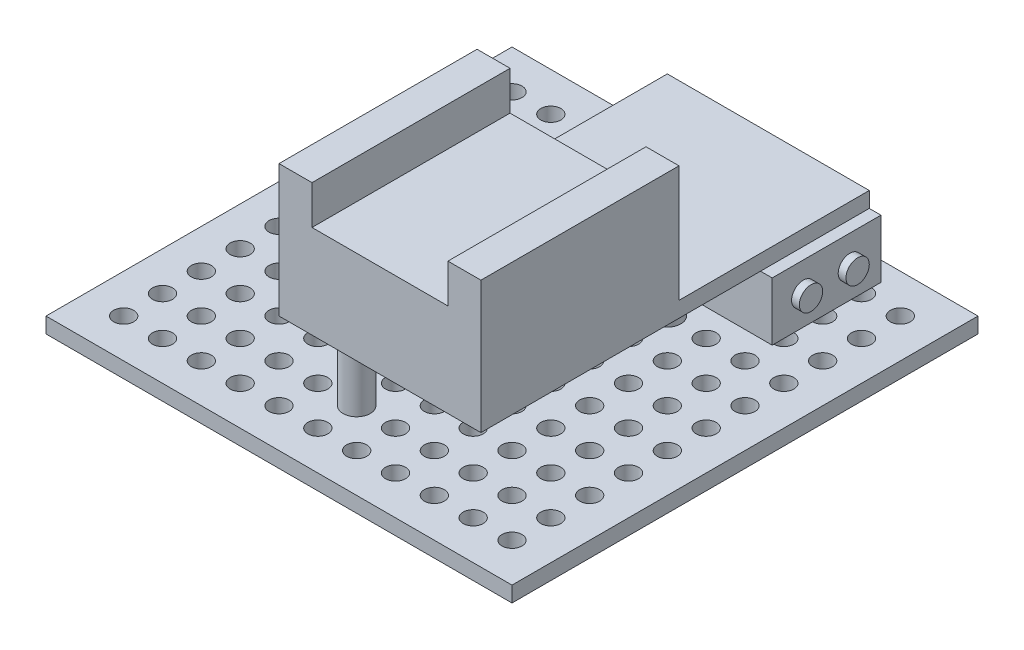
SolidWorks part; units mm, degrees
ref_plane "Front Plane" through (0, 0, 0) normal (0, 0, 1) x (1, 0, 0)
ref_plane "Top Plane" through (0, 0, 0) normal (0, 1, 0) x (1, 0, 0)
ref_plane "Right Plane" through (0, 0, 0) normal (1, 0, 0) x (0, 0, -1)
sketch "Sketch1" plane through (0, 0, 0) normal (0, 1, 0) x (1, 0, 0)
  line L1 (-60, -60) -> (60, -60)
  line L2 (-60, -60) -> (-60, 60)
  line L3 (-60, 60) -> (60, 60)
  line L4 (60, -60) -> (60, 60)
  line L5 (-60, -60) -> (60, 60) construction
  line L6 (-60, 60) -> (60, -60) construction
  point P0 (0, 0)
  dimension "D1" = 120
  dimension "D2" = 120
extrude "Boss-Extrude1" add sketch "Sketch1" along normal blind 4
hole_wizard "13/64 (0.20313) Diameter Hole1" positions "Sketch2" profile "Sketch3" hole size "13/64" standard "ANSI Inch" end condition up to next
sketch "Sketch2" plane through (0, 4, 0) normal (0, 1, 0) x (1, 0, 0)
  line L0 (-60, 60) -> (-60, -60) construction
  line L1 (60, 60) -> (-60, 60) construction
  point P0 (-50, 50)
  dimension "D1" = 10
  dimension "D2" = 10
sketch "Sketch3" plane through (-50, 4, -50) normal (1, 0, 0) x (0, 0, 1)
  line L0 (0, 0) -> (0, 4)
  line L1 (0, 4) -> (2.5798, 4)
  line L2 (2.5798, 4) -> (2.5798, 0)
  line L5 (2.5798, 0) -> (0, 0)
  line L11 (0, -6.35) -> (0, 107.95) construction
  dimension "Thru Hole Dia." = 5.1595
  dimension "Thru Hole Depth" = 4
pattern_linear "LPattern1" count 11 spacing 10 along (0, 0, 1) count 11 spacing 10 along (1, 0, 0) of "13/64 (0.20313) Diameter Hole1"
sketch "Sketch4" plane through (0, 4, 0) normal (0, 1, 0) x (1, 0, 0)
  line L0 (60, -60) -> (60, 60) construction
  line L1 (-60, -60) -> (60, -60) construction
  circle A0 centre (0, -40) radius 3.5
  circle A1 centre (0, 20) radius 3.5
  circle A2 centre (20, 20) radius 3.5
  point P10 (0, 0)
  point P11 (0, 0)
  dimension "D2" = 7
  dimension "D1" = 60
  dimension "D3" = 20
  dimension "D4" = 60
  dimension "D5" = 20
extrude "Boss-Extrude2" add sketch "Sketch4" along normal blind 20
sketch "Sketch5" plane through (0, 24, 0) normal (0, 1, 0) x (1, 0, 0)
  line L0 (60, -60) -> (60, 60) construction
  line L1 (-10, 50) -> (42, 50)
  line L2 (-10, 50) -> (-10, -50)
  line L3 (-10, -50) -> (42, -50)
  line L4 (42, 50) -> (42, -50)
  line L5 (-10, 50) -> (42, -50) construction
  line L6 (-10, -50) -> (42, 50) construction
  line L7 (-60, -60) -> (60, -60) construction
  point P4 (16, 0)
  point P5 (23.5, -3.5)
  dimension "D1" = 52
  dimension "D2" = 100
  dimension "D3" = 18
  dimension "D4" = 10
extrude "Boss-Extrude3" add sketch "Sketch5" along normal blind 4
sketch "Sketch6" plane through (0, 28, 0) normal (0, 1, 0) x (1, 0, 0)
  line L0 (42, -50) -> (42, 50) construction
  line L1 (-10, -50) -> (42, -50)
  line L2 (-10, -50) -> (-10, 1)
  line L3 (-10, 1) -> (42, 1)
  line L4 (42, -50) -> (42, 1)
  line L5 (-10, -50) -> (42, 1) construction
  line L6 (-10, 1) -> (42, -50) construction
  point P4 (16, -24.5)
  dimension "D1" = 51
extrude "Boss-Extrude4" add sketch "Sketch6" along normal blind 30
sketch "Sketch7" plane through (0, 58, 0) normal (0, 1, 0) x (1, 0, 0)
  line L0 (42, 1) -> (-10, 1) construction
  line L1 (-1.5, 1) -> (33.5, 1)
  line L2 (-1.5, 1) -> (-1.5, -50)
  line L3 (-1.5, -50) -> (33.5, -50)
  line L4 (33.5, 1) -> (33.5, -50)
  line L5 (-1.5, 1) -> (33.5, -50) construction
  line L6 (-1.5, -50) -> (33.5, 1) construction
  line L7 (-10, -50) -> (42, -50) construction
  point P4 (16, -24.5)
  point P9 (16, -50)
  dimension "D1" = 35
extrude "Cut-Extrude1" cut sketch "Sketch7" against normal blind 10
sketch "Sketch8" plane through (0, 4, 0) normal (0, 1, 0) x (1, 0, 0)
  line L0 (-31.9, 0) -> (31.9, 0) construction
  line L1 (5, 10) -> (-30, 10)
  line L2 (5, 10) -> (5, -10)
  line L3 (5, -10) -> (-30, -10)
  line L4 (-30, 10) -> (-30, -10)
  line L5 (5, 10) -> (-30, -10) construction
  line L6 (5, -10) -> (-30, 10) construction
  line L7 (-60, 60) -> (-60, -60) construction
  point P4 (-12.5, 0)
  point P5 (0, 0)
  dimension "D1" = 35
  dimension "D2" = 20
  dimension "D3" = 30
extrude "Boss-Extrude5" add sketch "Sketch8" along normal blind 4
sketch "Sketch9" plane through (0, 8, 0) normal (0, 1, 0) x (1, 0, 0)
  line L1 (-3.5, 3.5) -> (3.5, 3.5)
  line L2 (-3.5, 3.5) -> (-3.5, -3.5)
  line L3 (-3.5, -3.5) -> (3.5, -3.5)
  line L4 (3.5, 3.5) -> (3.5, -3.5)
  line L5 (-3.5, 3.5) -> (3.5, -3.5) construction
  line L6 (-3.5, -3.5) -> (3.5, 3.5) construction
  point P0 (0, 0)
  point P5 (0, 0)
  dimension "D1" = 7
extrude "Boss-Extrude6" add sketch "Sketch9" along normal blind 2
sketch "Sketch10" plane through (0, 4, 0) normal (0, 1, 0) x (1, 0, 0)
  line L0 (60, -60) -> (60, 60) construction
  line L1 (-5, 27) -> (40, 27)
  line L2 (-5, 27) -> (-5, 55)
  line L3 (-5, 55) -> (40, 55)
  line L4 (40, 27) -> (40, 55)
  line L5 (-5, 27) -> (40, 55) construction
  line L6 (-5, 55) -> (40, 27) construction
  line L7 (60, 60) -> (-60, 60) construction
  point P4 (17.5, 41)
  dimension "D1" = 45
  dimension "D2" = 28
  dimension "D3" = 20
  dimension "D4" = 5
extrude "Boss-Extrude7" add sketch "Sketch10" along normal blind 15
sketch "Sketch11" plane through (40, 0, 0) normal (1, 0, 0) x (0, 0, -1)
  line L0 (27, 11.5) -> (35, 11.5) construction
  line L1 (27, 19) -> (27, 4) construction
  line L2 (35, 11.5) -> (47, 11.5) construction
  line L3 (47, 11.5) -> (55, 11.5) construction
  line L4 (55, 19) -> (55, 4) construction
  circle A0 centre (35, 11.5) radius 3
  circle A1 centre (47, 11.5) radius 3
  dimension "D1" = 6
  dimension "D2" = 12
extrude "Boss-Extrude8" add sketch "Sketch11" along normal blind 2
